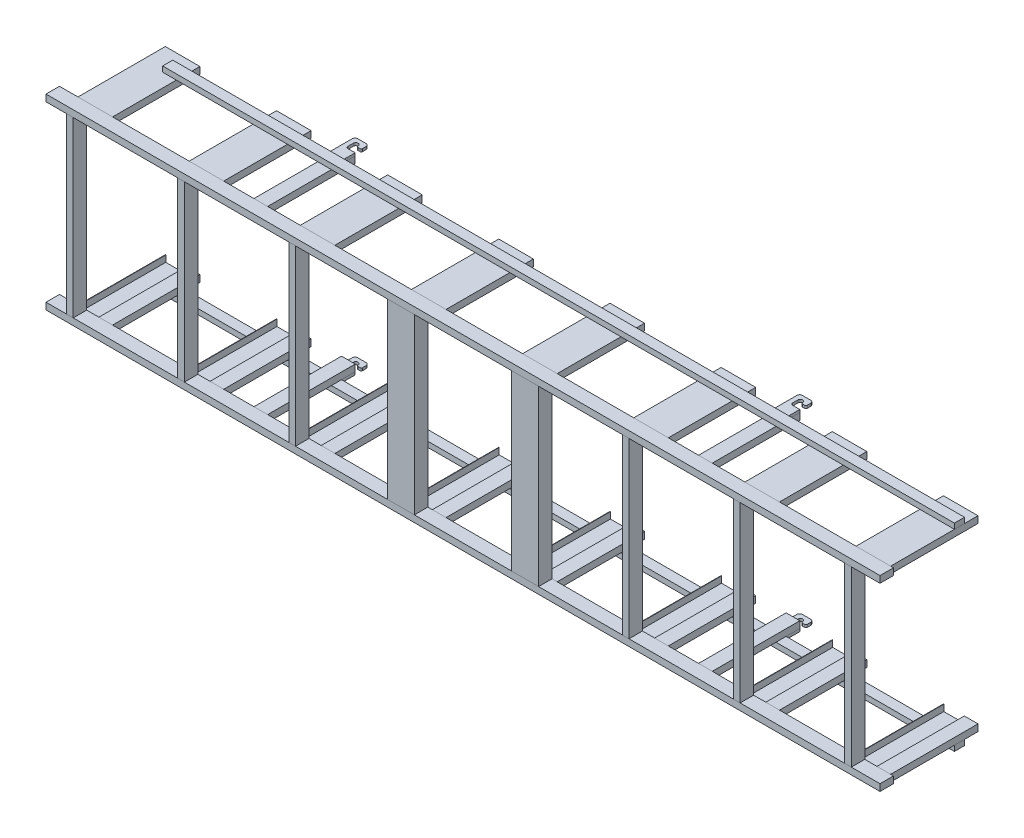
SolidWorks part; units mm, degrees
ref_plane "Front Plane" through (0, 0, 0) normal (0, 0, 1) x (1, 0, 0)
ref_plane "Top Plane" through (0, 0, 0) normal (0, 1, 0) x (1, 0, 0)
ref_plane "Right Plane" through (0, 0, 0) normal (1, 0, 0) x (0, 0, -1)
sketch "Sketch1" plane through (0, 0, 0) normal (0, 0, 1) x (1, 0, 0)
  line L0 (0, 1388) -> (6190, 1388)
  line L1 (0, 50) -> (6190, 50)
  line L2 (0, 50) -> (0, 0)
  line L3 (0, 0) -> (6190, 0)
  line L4 (6190, 50) -> (6190, 0)
  line L5 (0, 1388) -> (0, 1338)
  line L6 (0, 1338) -> (6190, 1338)
  line L7 (6190, 1388) -> (6190, 1338)
  dimension "D1" = 1288
  dimension "D2" = 50
extrude "Boss-Extrude1" add sketch "Sketch1" along normal blind 100
sketch "Sketch2" plane through (0, 0, 0) normal (0, -1, 0) x (1, 0, 0)
  line L0 (0, 100) -> (6190, 100) construction
  line L1 (2534, 100) -> (2734, 100)
  line L2 (2534, 100) -> (2534, 0)
  line L3 (2534, 0) -> (2734, 0)
  line L4 (2734, 100) -> (2734, 0)
  line L5 (0, 0) -> (6190, 0) construction
  line L6 (0, 100) -> (0, 0) construction
  line L8 (3456, 100) -> (3656, 100)
  line L9 (3456, 100) -> (3456, 0)
  line L10 (3456, 0) -> (3656, 0)
  line L11 (3656, 100) -> (3656, 0)
  point P8 (0, 50)
  dimension "D1" = 200
  dimension "D2" = 2534
  dimension "D3" = 2534
  dimension "D4" = 200
extrude "Boss-Extrude2" add sketch "Sketch2" against normal up to surface (1388 mm away) separate body up to face at (3095, 1388, 50)
sketch "Sketch3" plane through (0, 1388, 0) normal (0, 1, 0) x (1, 0, 0)
  line L2 (0, -100) -> (0, 0) construction
  line L3 (6190, -100) -> (6190, 0) construction
  line L12 (2541, -7) -> (2727, -7)
  line L13 (2727, -7) -> (2727, -93)
  line L14 (2541, -93) -> (2727, -93)
  line L15 (2541, -7) -> (2541, -93)
  line L16 (3463, -7) -> (3649, -7)
  line L17 (3649, -7) -> (3649, -93)
  line L18 (3463, -93) -> (3649, -93)
  line L19 (3463, -7) -> (3463, -93)
  point P2 (6190, -50)
  dimension "D1" = 186
  dimension "D2" = 186
  dimension "D3" = 2541
  dimension "D4" = 2541
sketch "Sketch4" plane through (0, 50, 0) normal (0, 1, 0) x (1, 0, 0)
  line L0 (6190, 0) -> (0, 0) construction
  line L1 (152, 0) -> (202, 0)
  line L2 (152, 0) -> (152, -100)
  line L3 (152, -100) -> (202, -100)
  line L4 (202, 0) -> (202, -100)
  line L5 (6190, -100) -> (0, -100) construction
  line L6 (0, -100) -> (0, 0) construction
  line L7 (977, 0) -> (977, -100)
  line L8 (977, 0) -> (1027, 0)
  line L9 (1027, 0) -> (1027, -100)
  line L10 (977, -100) -> (1027, -100)
  line L11 (1802, 0) -> (1802, -100)
  line L12 (1802, 0) -> (1852, 0)
  line L13 (1852, 0) -> (1852, -100)
  line L14 (1802, -100) -> (1852, -100)
  line L15 (2627, 0) -> (2627, -100) construction
  line L16 (2627, 0) -> (2677, 0) construction
  line L17 (2677, 0) -> (2677, -100) construction
  line L18 (2627, -100) -> (2677, -100) construction
  line L19 (3452, 0) -> (3452, -100) construction
  line L20 (3452, 0) -> (3502, 0) construction
  line L21 (3502, 0) -> (3502, -100) construction
  line L22 (3452, -100) -> (3502, -100) construction
  line L23 (4277, 0) -> (4277, -100)
  line L24 (4277, 0) -> (4327, 0)
  line L25 (4327, 0) -> (4327, -100)
  line L26 (4277, -100) -> (4327, -100)
  line L27 (5102, 0) -> (5102, -100)
  line L28 (5102, 0) -> (5152, 0)
  line L29 (5152, 0) -> (5152, -100)
  line L30 (5102, -100) -> (5152, -100)
  line L31 (5927, 0) -> (5927, -100)
  line L32 (5927, 0) -> (5977, 0)
  line L33 (5977, 0) -> (5977, -100)
  line L34 (5927, -100) -> (5977, -100)
  dimension "D1" = 152
  dimension "D2" = 50
  dimension "D3" = 8
extrude "Boss-Extrude3" add sketch "Sketch4" along normal up to next separate body
sketch "Sketch5" plane through (0, 0, 0) normal (0, 0, 1) x (1, 0, 0)
  line L0 (137.4, 1388) -> (137.4, 1338)
  line L1 (140.4, 1385.8) -> (140.4, 1338)
  line L2 (292.4, 1385.8) -> (140.4, 1385.8)
  line L3 (394, 1388) -> (394, 1338)
  line L4 (137.4, 1388) -> (394, 1388)
  line L5 (394, 1338) -> (292.4, 1338)
  line L6 (140.4, 1338) -> (137.4, 1338)
  line L7 (292.4, 1385.8) -> (292.4, 1338)
  line L10 (962.4, 1388) -> (962.4, 1338)
  line L11 (965.4, 1385.8) -> (965.4, 1338)
  line L12 (1117.4, 1385.8) -> (965.4, 1385.8)
  line L13 (1219, 1388) -> (1219, 1338)
  line L14 (962.4, 1388) -> (1219, 1388)
  line L15 (1219, 1338) -> (1117.4, 1338)
  line L16 (965.4, 1338) -> (962.4, 1338)
  line L17 (1117.4, 1385.8) -> (1117.4, 1338)
  line L19 (1787.4, 1388) -> (1787.4, 1338)
  line L20 (1790.4, 1385.8) -> (1790.4, 1338)
  line L21 (1942.4, 1385.8) -> (1790.4, 1385.8)
  line L22 (2044, 1388) -> (2044, 1338)
  line L23 (1787.4, 1388) -> (2044, 1388)
  line L24 (2044, 1338) -> (1942.4, 1338)
  line L25 (1790.4, 1338) -> (1787.4, 1338)
  line L26 (1942.4, 1385.8) -> (1942.4, 1338)
  line L28 (2612.4, 1388) -> (2612.4, 1338)
  line L29 (2615.4, 1385.8) -> (2615.4, 1338)
  line L30 (2767.4, 1385.8) -> (2615.4, 1385.8)
  line L31 (2869, 1388) -> (2869, 1338)
  line L32 (2612.4, 1388) -> (2869, 1388)
  line L33 (2869, 1338) -> (2767.4, 1338)
  line L34 (2615.4, 1338) -> (2612.4, 1338)
  line L35 (2767.4, 1385.8) -> (2767.4, 1338)
  line L36 (2627, 1338) -> (2612.4, 1338) construction
  line L37 (3437.4, 1388) -> (3437.4, 1338)
  line L38 (3440.4, 1385.8) -> (3440.4, 1338)
  line L39 (3592.4, 1385.8) -> (3440.4, 1385.8)
  line L40 (3694, 1388) -> (3694, 1338)
  line L41 (3437.4, 1388) -> (3694, 1388)
  line L42 (3694, 1338) -> (3592.4, 1338)
  line L43 (3440.4, 1338) -> (3437.4, 1338)
  line L44 (3592.4, 1385.8) -> (3592.4, 1338)
  line L45 (3452, 1338) -> (3437.4, 1338) construction
  line L46 (4262.4, 1388) -> (4262.4, 1338)
  line L47 (4265.4, 1385.8) -> (4265.4, 1338)
  line L48 (4417.4, 1385.8) -> (4265.4, 1385.8)
  line L49 (4519, 1388) -> (4519, 1338)
  line L50 (4262.4, 1388) -> (4519, 1388)
  line L51 (4519, 1338) -> (4417.4, 1338)
  line L52 (4265.4, 1338) -> (4262.4, 1338)
  line L53 (4417.4, 1385.8) -> (4417.4, 1338)
  line L54 (4277, 1338) -> (4262.4, 1338) construction
  line L55 (5087.4, 1388) -> (5087.4, 1338)
  line L56 (5090.4, 1385.8) -> (5090.4, 1338)
  line L57 (5242.4, 1385.8) -> (5090.4, 1385.8)
  line L58 (5344, 1388) -> (5344, 1338)
  line L59 (5087.4, 1388) -> (5344, 1388)
  line L60 (5344, 1338) -> (5242.4, 1338)
  line L61 (5090.4, 1338) -> (5087.4, 1338)
  line L62 (5242.4, 1385.8) -> (5242.4, 1338)
  line L64 (5912.4, 1388) -> (5912.4, 1338)
  line L65 (5915.4, 1385.8) -> (5915.4, 1338)
  line L66 (6067.4, 1385.8) -> (5915.4, 1385.8)
  line L67 (6169, 1388) -> (6169, 1338)
  line L68 (5912.4, 1388) -> (6169, 1388)
  line L69 (6169, 1338) -> (6067.4, 1338)
  line L70 (5915.4, 1338) -> (5912.4, 1338)
  line L71 (6067.4, 1385.8) -> (6067.4, 1338)
  line L73 (152, 694) -> (5977, 694) construction
  line L74 (152, 1338) -> (152, 50) construction
  line L75 (5977, 1338) -> (5977, 50) construction
  line L79 (3452, 50) -> (3437.4, 50) construction
  line L80 (2627, 50) -> (2612.4, 50) construction
  line L84 (6067.4, 2.2) -> (6067.4, 50)
  line L85 (5915.4, 50) -> (5912.4, 50)
  line L86 (6169, 50) -> (6067.4, 50)
  line L87 (5912.4, 0) -> (6169, 0)
  line L88 (6169, 0) -> (6169, 50)
  line L89 (6067.4, 2.2) -> (5915.4, 2.2)
  line L90 (5915.4, 2.2) -> (5915.4, 50)
  line L91 (5912.4, 0) -> (5912.4, 50)
  line L92 (5242.4, 2.2) -> (5242.4, 50)
  line L93 (5090.4, 50) -> (5087.4, 50)
  line L94 (5344, 50) -> (5242.4, 50)
  line L95 (5087.4, 0) -> (5344, 0)
  line L96 (5344, 0) -> (5344, 50)
  line L97 (5242.4, 2.2) -> (5090.4, 2.2)
  line L98 (5090.4, 2.2) -> (5090.4, 50)
  line L99 (5087.4, 0) -> (5087.4, 50)
  line L100 (4417.4, 2.2) -> (4417.4, 50)
  line L101 (4265.4, 50) -> (4262.4, 50)
  line L102 (4519, 50) -> (4417.4, 50)
  line L103 (4262.4, 0) -> (4519, 0)
  line L104 (4519, 0) -> (4519, 50)
  line L105 (4417.4, 2.2) -> (4265.4, 2.2)
  line L106 (4265.4, 2.2) -> (4265.4, 50)
  line L107 (4262.4, 0) -> (4262.4, 50)
  line L108 (3592.4, 2.2) -> (3592.4, 50)
  line L109 (3440.4, 50) -> (3437.4, 50)
  line L110 (3694, 50) -> (3592.4, 50)
  line L111 (3437.4, 0) -> (3694, 0)
  line L112 (3694, 0) -> (3694, 50)
  line L113 (3592.4, 2.2) -> (3440.4, 2.2)
  line L114 (3440.4, 2.2) -> (3440.4, 50)
  line L115 (3437.4, 0) -> (3437.4, 50)
  line L116 (2767.4, 2.2) -> (2767.4, 50)
  line L117 (2615.4, 50) -> (2612.4, 50)
  line L118 (2869, 50) -> (2767.4, 50)
  line L119 (2612.4, 0) -> (2869, 0)
  line L120 (2869, 0) -> (2869, 50)
  line L121 (2767.4, 2.2) -> (2615.4, 2.2)
  line L122 (2615.4, 2.2) -> (2615.4, 50)
  line L123 (2612.4, 0) -> (2612.4, 50)
  line L124 (1942.4, 2.2) -> (1942.4, 50)
  line L125 (1790.4, 50) -> (1787.4, 50)
  line L126 (2044, 50) -> (1942.4, 50)
  line L127 (1787.4, 0) -> (2044, 0)
  line L128 (2044, 0) -> (2044, 50)
  line L129 (1942.4, 2.2) -> (1790.4, 2.2)
  line L130 (1790.4, 2.2) -> (1790.4, 50)
  line L131 (1787.4, 0) -> (1787.4, 50)
  line L132 (1117.4, 2.2) -> (1117.4, 50)
  line L133 (965.4, 50) -> (962.4, 50)
  line L134 (1219, 50) -> (1117.4, 50)
  line L135 (962.4, 0) -> (1219, 0)
  line L136 (1219, 0) -> (1219, 50)
  line L137 (1117.4, 2.2) -> (965.4, 2.2)
  line L138 (965.4, 2.2) -> (965.4, 50)
  line L139 (962.4, 0) -> (962.4, 50)
  line L140 (292.4, 2.2) -> (292.4, 50)
  line L141 (140.4, 50) -> (137.4, 50)
  line L142 (394, 50) -> (292.4, 50)
  line L143 (137.4, 0) -> (394, 0)
  line L144 (394, 0) -> (394, 50)
  line L145 (292.4, 2.2) -> (140.4, 2.2)
  line L146 (140.4, 2.2) -> (140.4, 50)
  line L147 (137.4, 0) -> (137.4, 50)
extrude "Boss-Extrude4" add sketch "Sketch5" against normal blind 648.4 separate body
sketch "Sketch8" plane through (0, 50, 0) normal (0, 1, 0) x (1, 0, 0)
  line L0 (1443.4, 0) -> (1443.4, 650) construction
  line L1 (1443.4, 650) -> (1545, 650) construction
  line L2 (1545, 650) -> (4743.4, 650) construction
  line L4 (1545, 0) -> (1443.4, 0)
  line L5 (1443.4, 0) -> (1443.4, 650)
  line L6 (1545, 0) -> (1545, 650)
  line L8 (0, 0) -> (1443.4, 0) construction
  line L9 (6190, 0) -> (4845, 0) construction
  line L10 (4845, 0) -> (4743.4, 0)
  line L11 (4743.4, 650) -> (4845, 650)
  line L14 (4743.4, 0) -> (4743.4, 650)
  line L15 (4845, 0) -> (4845, 650)
  line L19 (1443.4, 650) -> (1545, 650)
extrude "Boss-Extrude5" add sketch "Sketch8" against normal blind 50 separate body
sketch "Sketch9" plane through (0, 1388, 0) normal (0, 1, 0) x (1, 0, 0)
  line L0 (1443.4, 0) -> (1443.4, 650) construction
  line L1 (1443.4, 650) -> (1545, 650) construction
  line L2 (1545, 650) -> (4743.4, 650) construction
  line L3 (1545, 0) -> (1443.4, 0)
  line L4 (1443.4, 0) -> (1443.4, 650)
  line L5 (1545, 0) -> (1545, 650)
  line L6 (4845, 0) -> (4743.4, 0)
  line L7 (4743.4, 650) -> (4845, 650)
  line L10 (4743.4, 0) -> (4743.4, 650)
  line L11 (4845, 0) -> (4845, 650)
  line L12 (1443.4, 650) -> (1545, 650)
extrude "Boss-Extrude6" add sketch "Sketch9" against normal blind 50 separate body
sketch "Sketch10" plane through (6169, 0, 0) normal (1, 0, 0) x (0, 0, -1)
  line L0 (648.4, 0) -> (0, 0) construction
  line L1 (548.4, 0) -> (473.4, 0)
  line L2 (548.4, 0) -> (548.4, -40)
  line L3 (548.4, -40) -> (473.4, -40)
  line L4 (473.4, 0) -> (473.4, -40)
  line L5 (648.4, 1388) -> (0, 1388) construction
  line L6 (548.4, 1388) -> (473.4, 1388)
  line L7 (548.4, 1388) -> (548.4, 1428)
  line L8 (548.4, 1428) -> (473.4, 1428)
  line L9 (473.4, 1388) -> (473.4, 1428)
  dimension "D1" = 100
  dimension "D2" = 75
  dimension "D3" = 75
  dimension "D4" = 100
extrude "Boss-Extrude7" add sketch "Sketch10" against normal up to surface (5876.6 mm away) separate body up to face at (292.4, 1361.9, -324.2)
sketch "Sketch11" plane through (0, 0, 0) normal (0, -1, 0) x (1, 0, 0)
  line L0 (4845, -650) -> (4791.2629, -650)
  line L1 (1443.2116, -729.6096) -> (1443.2116, -869.6954) construction
  line L2 (1545, -650) -> (1545, -550) construction
  line L3 (1545, -650) -> (1491.2629, -650)
  line L4 (1535.3629, -695) -> (1521.2629, -695)
  line L5 (1545.3629, -730) -> (1545.3629, -705)
  line L6 (4825.3629, -750) -> (4763.7629, -750)
  line L7 (1476.2629, -705) -> (1476.2629, -665)
  line L8 (4776.2629, -705) -> (4776.2629, -665)
  line L9 (4835.3629, -695) -> (4821.2629, -695)
  line L10 (4845, -550) -> (4743.4, -550)
  line L11 (4743.2116, -729.6096) -> (4743.2116, -869.6954) construction
  line L12 (4845, -650) -> (4845, -550) construction
  line L13 (4845, -650) -> (4845, -550)
  line L14 (4845.3629, -730) -> (4845.3629, -705)
  line L15 (1525.3629, -750) -> (1463.7629, -750)
  line L16 (1545, -650) -> (1545, -550)
  line L17 (1443.4, -730) -> (1443.4, -550)
  line L18 (1545, -550) -> (1443.4, -550)
  line L19 (4743.4, -730) -> (4743.4, -550)
  arc A0 (1491.2629, -650) -> (1476.2629, -665) centre (1491.2629, -665) ccw
  arc A1 (1545.3629, -705) -> (1535.3629, -695) centre (1535.3629, -705) ccw
  arc A2 (1525.3629, -750) -> (1545.3629, -730) centre (1525.3629, -730) ccw
  arc A3 (1443.4, -730) -> (1463.7629, -750) centre (1463.5212, -729.8799) ccw
  arc A4 (1476.2629, -705) -> (1511.2629, -705) centre (1493.7629, -705) ccw
  arc A5 (1521.2629, -695) -> (1511.2629, -705) centre (1521.2629, -705) ccw
  arc A6 (4743.4, -730) -> (4763.7629, -750) centre (4763.5212, -729.8799) ccw
  arc A7 (4845.3629, -705) -> (4835.3629, -695) centre (4835.3629, -705) ccw
  arc A8 (4791.2629, -650) -> (4776.2629, -665) centre (4791.2629, -665) ccw
  arc A9 (4776.2629, -705) -> (4811.2629, -705) centre (4793.7629, -705) ccw
  arc A10 (4825.3629, -750) -> (4845.3629, -730) centre (4825.3629, -730) ccw
  arc A11 (4821.2629, -695) -> (4811.2629, -705) centre (4821.2629, -705) ccw
extrude "Boss-Extrude8" add sketch "Sketch11" along normal blind 20 separate body
sketch "Sketch12" plane through (0, 1388, 0) normal (0, 1, 0) x (1, 0, 0)
  line L1 (1443.2116, 570.3907) -> (1443.2116, 430.3049) construction
  line L11 (4743.2116, 570.3907) -> (4743.2116, 430.3049) construction
  line L20 (1545, 650.0002) -> (1715.2808, 650.0002) construction
  line L21 (4845, 650.0002) -> (4845, 550.0002) construction
  line L22 (4743.4, 730.0002) -> (4743.4, 550.0002)
  line L23 (4845.3629, 730.0002) -> (4845.3629, 705.0002)
  line L24 (4845, 650.0002) -> (4845, 550.0002)
  line L25 (4845, 550.0002) -> (4743.4, 550.0002)
  line L26 (4835.3629, 695.0002) -> (4821.2629, 695.0002)
  line L27 (4776.2629, 705.0002) -> (4776.2629, 665.0002)
  line L28 (4825.3629, 750.0002) -> (4763.7629, 750.0002)
  line L29 (4845, 650.0002) -> (4791.2629, 650.0002)
  line L30 (1545, 650.0002) -> (1545, 550.0002) construction
  line L31 (1545, 550.0002) -> (1443.4, 550.0002)
  line L32 (1443.4, 730.0002) -> (1443.4, 550.0002)
  line L33 (1545, 650.0002) -> (1545, 550.0002)
  line L34 (1525.3629, 750.0002) -> (1463.7629, 750.0002)
  line L35 (1476.2629, 705.0002) -> (1476.2629, 665.0002)
  line L36 (1545.3629, 730.0002) -> (1545.3629, 705.0002)
  line L37 (1535.3629, 695.0002) -> (1521.2629, 695.0002)
  line L38 (1545, 650.0002) -> (1491.2629, 650.0002)
  arc A12 (4821.2629, 695.0002) -> (4811.2629, 705.0002) centre (4821.2629, 705.0002) cw
  arc A13 (4825.3629, 750.0002) -> (4845.3629, 730.0002) centre (4825.3629, 730.0002) cw
  arc A14 (4776.2629, 705.0002) -> (4811.2629, 705.0002) centre (4793.7629, 705.0002) cw
  arc A15 (4791.2629, 650.0002) -> (4776.2629, 665.0002) centre (4791.2629, 665.0002) cw
  arc A16 (4845.3629, 705.0002) -> (4835.3629, 695.0002) centre (4835.3629, 705.0002) cw
  arc A17 (4743.4, 730.0002) -> (4763.7629, 750.0002) centre (4763.5212, 729.8801) cw
  arc A18 (1521.2629, 695.0002) -> (1511.2629, 705.0002) centre (1521.2629, 705.0002) cw
  arc A19 (1476.2629, 705.0002) -> (1511.2629, 705.0002) centre (1493.7629, 705.0002) cw
  arc A20 (1443.4, 730.0002) -> (1463.7629, 750.0002) centre (1463.5212, 729.8801) cw
  arc A21 (1525.3629, 750.0002) -> (1545.3629, 730.0002) centre (1525.3629, 730.0002) cw
  arc A22 (1545.3629, 705.0002) -> (1535.3629, 695.0002) centre (1535.3629, 705.0002) cw
  arc A23 (1491.2629, 650.0002) -> (1476.2629, 665.0002) centre (1491.2629, 665.0002) cw
extrude "Boss-Extrude9" add sketch "Sketch12" along normal blind 20 separate body
